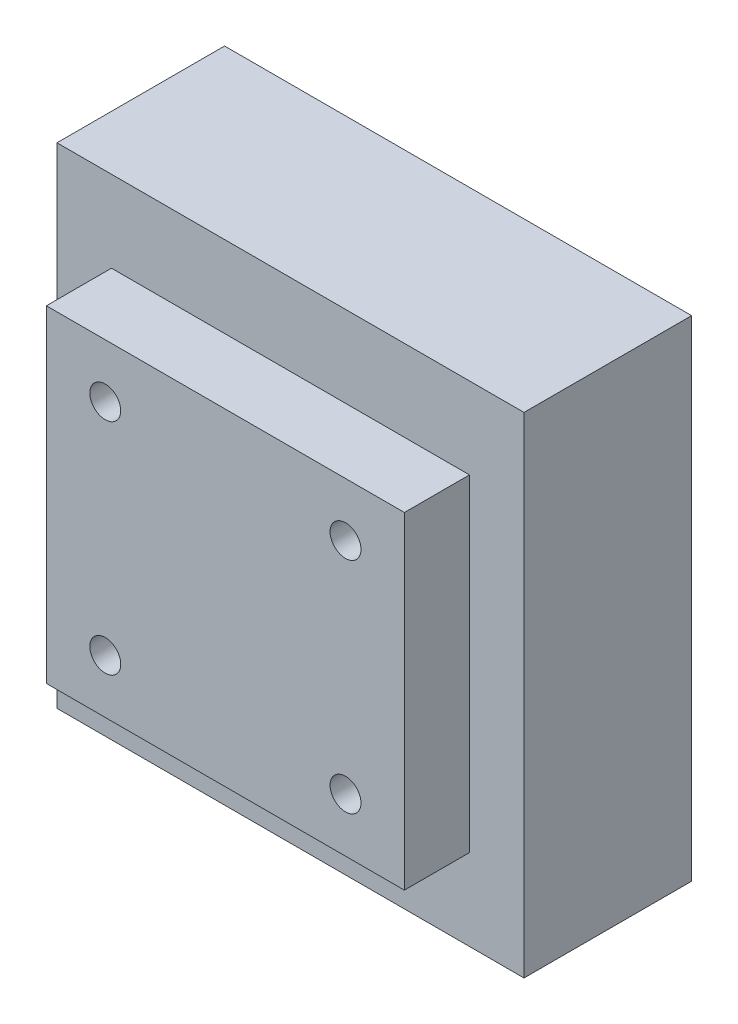
SolidWorks part; units mm, degrees
ref_plane "Front Plane" through (0, 0, 0) normal (0, 0, 1) x (1, 0, 0)
ref_plane "Top Plane" through (0, 0, 0) normal (0, 1, 0) x (1, 0, 0)
ref_plane "Right Plane" through (0, 0, 0) normal (1, 0, 0) x (0, 0, -1)
sketch "Sketch1" plane through (0, 0, 0) normal (0, 0, 1) x (1, 0, 0)
  line L1 (0, 0) -> (28.7, 0)
  line L2 (0, 0) -> (0, 30.1)
  line L3 (0, 30.1) -> (28.7, 30.1)
  line L4 (28.7, 0) -> (28.7, 30.1)
  dimension "D1" = 30.1
  dimension "D2" = 28.7
extrude "Boss-Extrude1" add sketch "Sketch1" along normal blind 10.3
sketch "Sketch2" plane through (0, 0, 10.3) normal (0, 0, 1) x (1, 0, 0)
  line L0 (0, 30.1) -> (28.7, 0) construction
  line L1 (14.35, 30.1) -> (14.35, 0) construction
  line L2 (28.7, 30.1) -> (0, 30.1) construction
  line L3 (0, 0) -> (28.7, 0) construction
  line L4 (25.35, 25.1) -> (3.35, 25.1)
  line L5 (0, 15.05) -> (28.7, 15.05) construction
  line L6 (0, 30.1) -> (0, 0) construction
  line L7 (28.7, 0) -> (28.7, 30.1) construction
  line L8 (3.35, 25.1) -> (3.35, 5)
  line L9 (25.35, 5) -> (3.35, 5)
  line L10 (25.35, 25.1) -> (25.35, 5)
  line L11 (3.35, 5) -> (25.35, 25.1) construction
  circle A0 centre (6.9673, 8.3049) radius 0.95
  circle A1 centre (6.9673, 21.7951) radius 0.95
  circle A2 centre (21.7327, 8.3049) radius 0.95
  circle A3 centre (21.7327, 21.7951) radius 0.95
  point P21 (3.35, 15.05)
  point P22 (14.35, 5)
  point P23 (14.35, 25.1)
  point P25 (14.35, 15.05)
  dimension "D3" = 1.9
  dimension "D1" = 11
  dimension "D2" = 5
  dimension "D4" = 10
extrude "Boss-Extrude2" add sketch "Sketch2" along normal blind 4
sketch "Sketch4" plane through (0, 0, 0) normal (0, 0, -1) x (-1, 0, 0)
  line L4 (0, 0) -> (0, 30.1)
  line L5 (0, 30.1) -> (-28.7, 30.1)
  line L6 (-28.7, 30.1) -> (-28.7, 0)
  line L7 (-28.7, 0) -> (0, 0)
  line L8 (0, 0) -> (0, 30.1)
  line L9 (0, 30.1) -> (-28.7, 30.1)
  line L10 (-28.7, 30.1) -> (-28.7, 0)
  line L11 (-28.7, 0) -> (0, 0)
  circle A0 centre (-21.7327, 21.7951) radius 0.95 construction
  circle A1 centre (-21.7327, 8.3049) radius 0.95 construction
  circle A2 centre (-6.9673, 8.3049) radius 0.95 construction
  circle A3 centre (-6.9673, 21.7951) radius 0.95 construction
  circle A4 centre (-21.7327, 21.7951) radius 0.95
  circle A5 centre (-21.7327, 8.3049) radius 0.95
  circle A6 centre (-6.9673, 8.3049) radius 0.95
  circle A7 centre (-6.9673, 21.7951) radius 0.95
  dimension "D1" = 0
extrude "Cut-Extrude1" cut sketch "Sketch4" against normal through all contours A7 | A4 | A5 | A6
